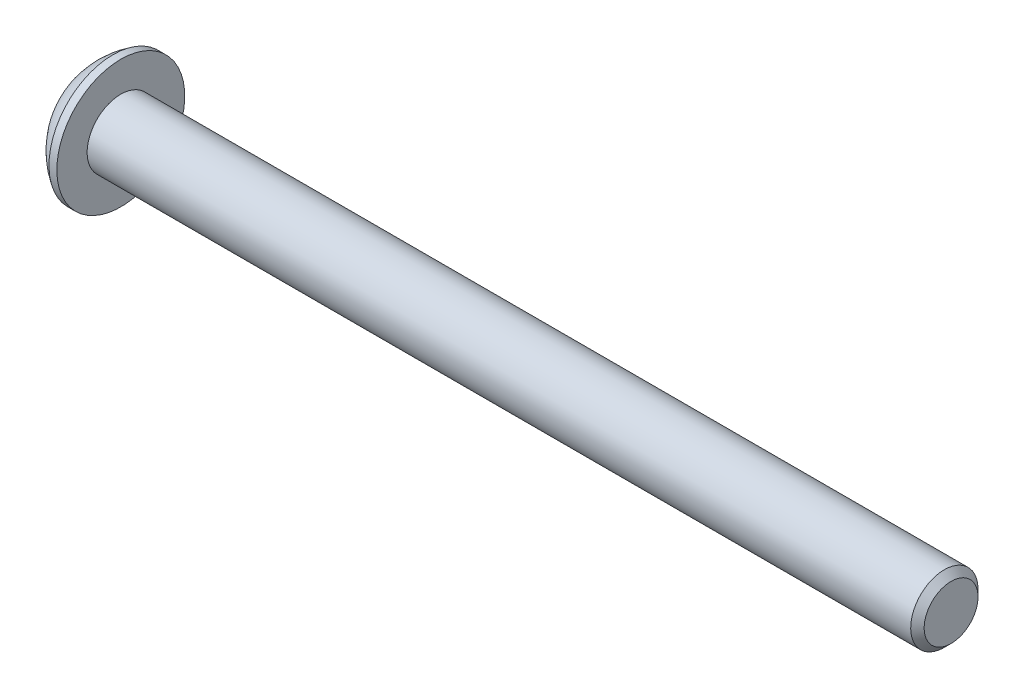
SolidWorks part; units mm, degrees
ref_plane "Front Plane" through (0, 0, 0) normal (0, 0, 1) x (1, 0, 0)
ref_plane "Top Plane" through (0, 0, 0) normal (0, 1, 0) x (1, 0, 0)
ref_plane "Right Plane" through (0, 0, 0) normal (1, 0, 0) x (0, 0, -1)
sketch "Sketch1" plane through (0, 0, 0) normal (0, 0, 1) x (1, 0, 0)
  line L0 (38.65, 0) -> (0, 0)
  line L1 (0, 0) -> (0, 1.425)
  line L2 (1.3, 2.85) -> (1.65, 2.85)
  line L3 (1.65, 2.85) -> (1.65, 1.5)
  line L4 (1.65, 1.5) -> (38.65, 1.5)
  line L5 (38.65, 1.5) -> (38.65, 0)
  arc A1 (1.3, 2.85) -> (0, 1.425) centre (3.1356, -0.13) ccw
  point P3 (1.65, 2.175)
  dimension "D6" = 3.5
  dimension "D1" = 37
  dimension "D2" = 1.5
  dimension "D3" = 2.85
  dimension "D4" = 0.35
  dimension "D5" = 1.65
  dimension "D7" = 1.425
revolve "Revolve1" add sketch "Sketch1" angle 360 about L0
chamfer "Chamfer1" distance 0.3 angle 45 1 edges at (38.65, 1.5, 0)
sketch "Sketch2" plane through (0, 0, 0) normal (-1, 0, 0) x (0, 0, 1)
  line L1 (0, 1.1547) -> (-1, 0.5774)
  line L2 (-1, 0.5774) -> (-1, -0.5774)
  line L3 (-1, -0.5774) -> (0, -1.1547)
  line L4 (0, -1.1547) -> (1, -0.5774)
  line L5 (1, -0.5774) -> (1, 0.5774)
  line L6 (1, 0.5774) -> (0, 1.1547)
  circle A0 centre (0, 0) radius 1 construction
  dimension "D1" = 2
extrude "Cut-Extrude1" cut sketch "Sketch2" against normal blind 1
